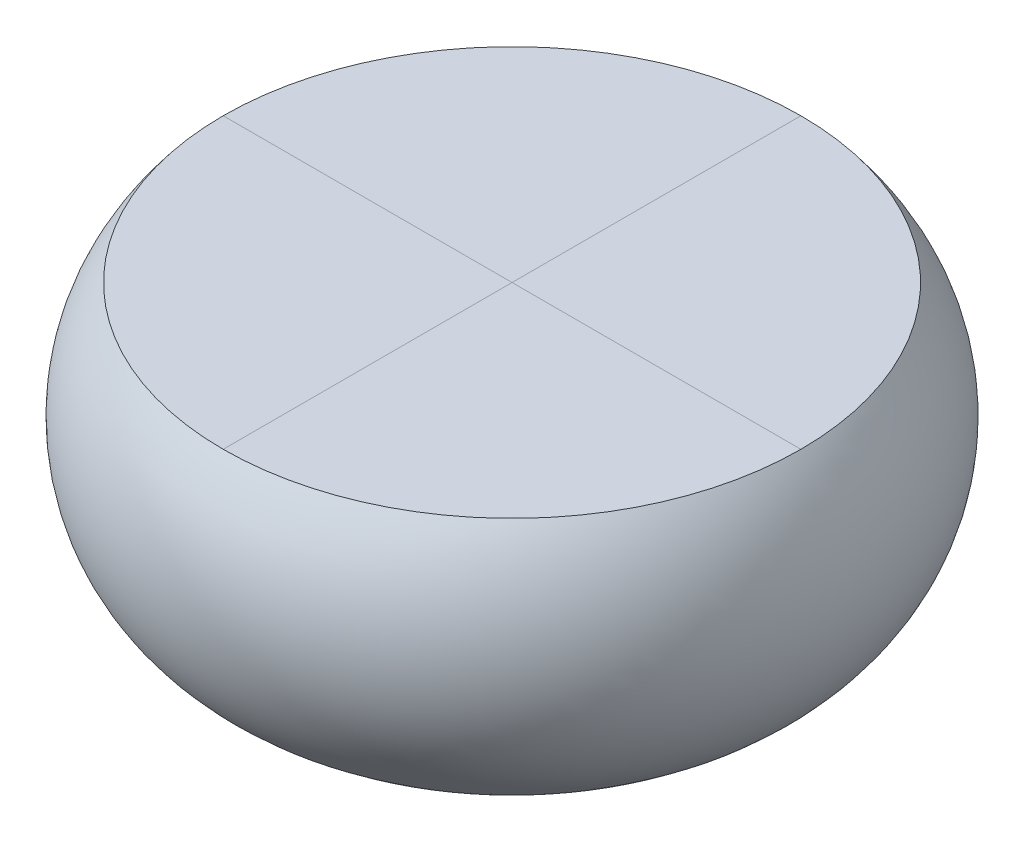
SolidWorks part; units mm, degrees
ref_plane "Front" through (0, 0, 0) normal (0, 0, 1) x (1, 0, 0)
ref_plane "Top" through (0, 0, 0) normal (0, 1, 0) x (1, 0, 0)
ref_plane "Right" through (0, 0, 0) normal (1, 0, 0) x (0, 0, -1)
sketch "Sketch1" plane through (0, 0, 0) normal (0, 0, 1) x (1, 0, 0)
  line L0 (0, 0) -> (70.9441, 0)
  line L1 (0, 197.0054) -> (0, -47.1361) construction
  line L2 (115.3502, 118.5941) -> (0, 118.5941)
  line L4 (0, 118.5941) -> (0, 0)
  arc A0 (70.9441, 0) -> (115.3502, 118.5941) centre (58.0136, 72.4524) ccw
  dimension "D1" = 70.9441
  dimension "D2" = 118.5941
  dimension "D3" = 115.3502
revolve "Revolve6" add sketch "Sketch1" angle 360 about L1
sketch "Sketch2" plane through (0, 118.5941, 0) normal (0, 1, 0) x (-1, 0, 0)
  line L0 (0, 163.675) -> (0, -159.9185)
split line "Split Line1"
sketch "Sketch3" plane through (0, 118.5941, 0) normal (0, 1, 0) x (-1, 0, 0)
  line L0 (-142.4777, 0) -> (140.8678, 0)
split line "Split Line2"
